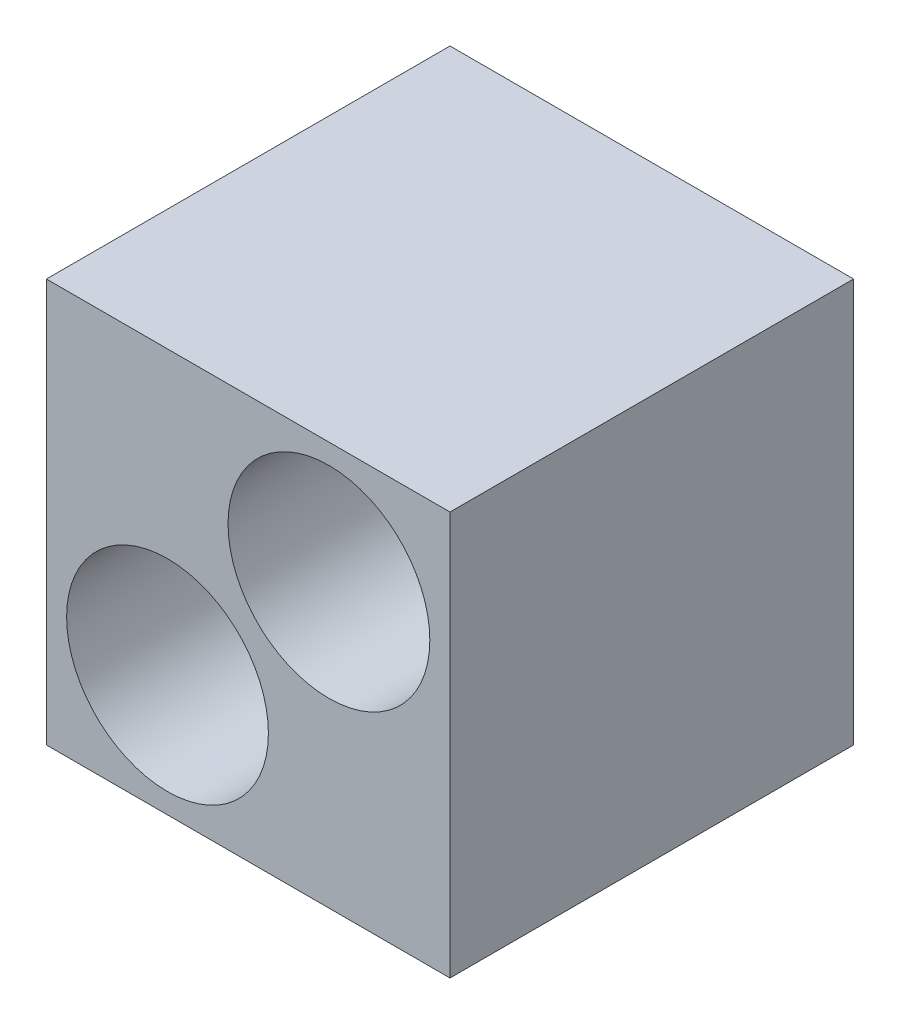
SolidWorks part; units mm, degrees
ref_plane "Front Plane" through (0, 0, 0) normal (0, 0, 1) x (1, 0, 0)
ref_plane "Top Plane" through (0, 0, 0) normal (0, 1, 0) x (1, 0, 0)
ref_plane "Right Plane" through (0, 0, 0) normal (1, 0, 0) x (0, 0, -1)
sketch "Sketch1" plane through (0, 0, 0) normal (0, 0, 1) x (1, 0, 0)
  line L1 (0, 0) -> (10, 0)
  line L2 (0, 0) -> (0, 10)
  line L3 (0, 10) -> (10, 10)
  line L4 (10, 0) -> (10, 10)
extrude "Boss-Extrude1" add sketch "Sketch1" along normal blind 10
sketch "Sketch2" plane through (0, 0, 0) normal (0, 0, 1) x (1, 0, 0)
  circle A0 centre (3, 3) radius 2.5
  circle A1 centre (7, 7) radius 2.5
extrude "Cut-Extrude1" cut sketch "Sketch2" along normal through all
